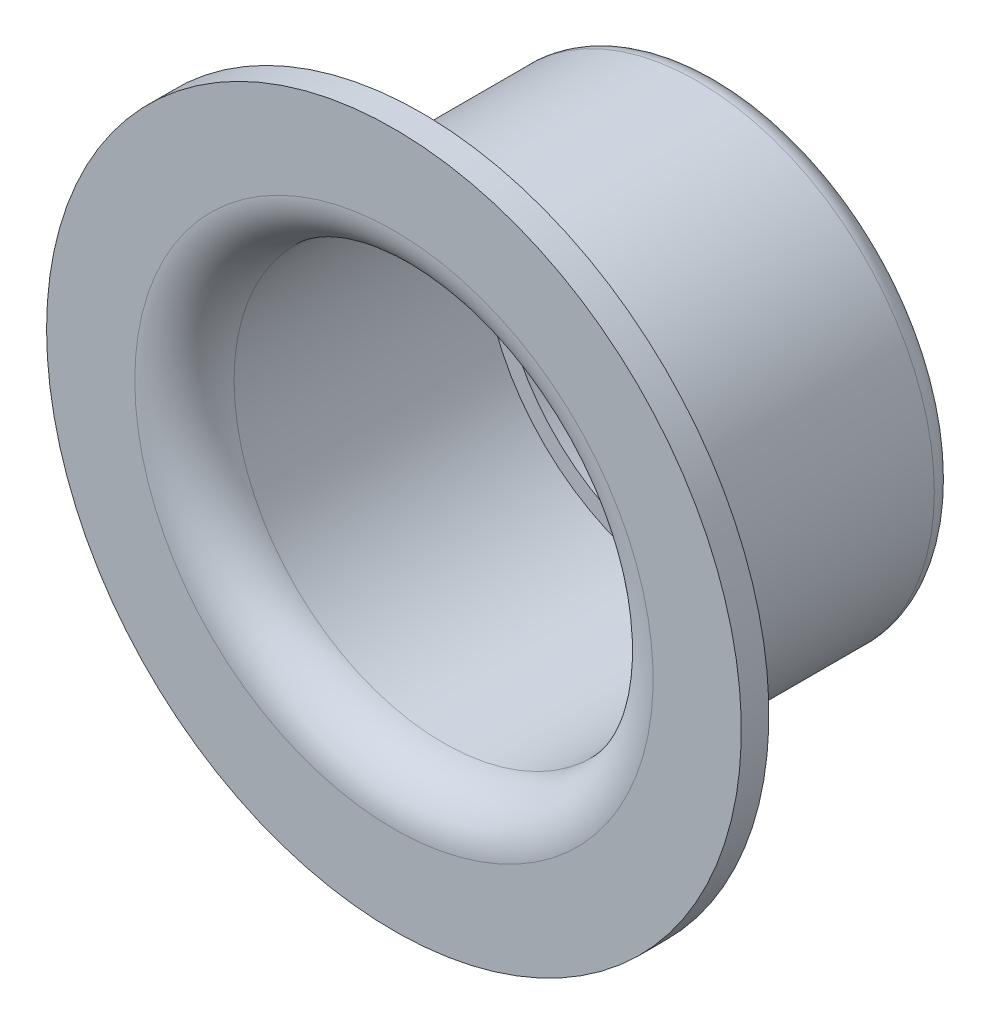
SolidWorks part; units mm, degrees
material "6061 Alloy"
ref_plane "Front Plane" through (0, 0, 0) normal (0, 0, 1) x (1, 0, 0)
ref_plane "Top Plane" through (0, 0, 0) normal (0, 1, 0) x (1, 0, 0)
ref_plane "Right Plane" through (0, 0, 0) normal (1, 0, 0) x (0, 0, -1)
sketch "Sketch1" plane through (0, 0, 0) normal (1, 0, 0) x (0, 0, -1)
  line L0 (0, 0) -> (-67.9722, 0) construction
  line L1 (0, 17.4625) -> (0, 19.5)
  line L2 (-2, 21.5) -> (-25, 21.5)
  line L3 (-27, 23.5) -> (-27, 31.5)
  line L4 (-27, 31.5) -> (-29.5, 31.5)
  line L5 (-2.5, 17.4625) -> (-2.5, 19)
  line L6 (-2.5, 19) -> (-25, 19)
  line L7 (-29.5, 23.5) -> (-29.5, 31.5)
  line L8 (0, 17.4625) -> (-2.5, 17.4625)
  line L9 (-29.5, 23.5) -> (-29.5, 29) construction
  line L10 (-29.5, 29) -> (-29.5, 29) construction
  arc A0 (0, 19.5) -> (-2, 21.5) centre (-2, 19.5) ccw
  arc A1 (-25, 21.5) -> (-27, 23.5) centre (-25, 23.5) cw
  arc A2 (-2.5, 19) -> (-2.5, 19) centre (-2.5, 19) ccw
  arc A3 (-25, 19) -> (-29.5, 23.5) centre (-25, 23.5) cw
  dimension "D1" = 2
  dimension "D2" = 2.5
  dimension "D3" = 17.4625
  dimension "D4" = 21.5
  dimension "D5" = 31.5
  dimension "D7" = 27
  dimension "D6" = 2.5
revolve "Revolve1" add sketch "Sketch1" angle 360 about L0
